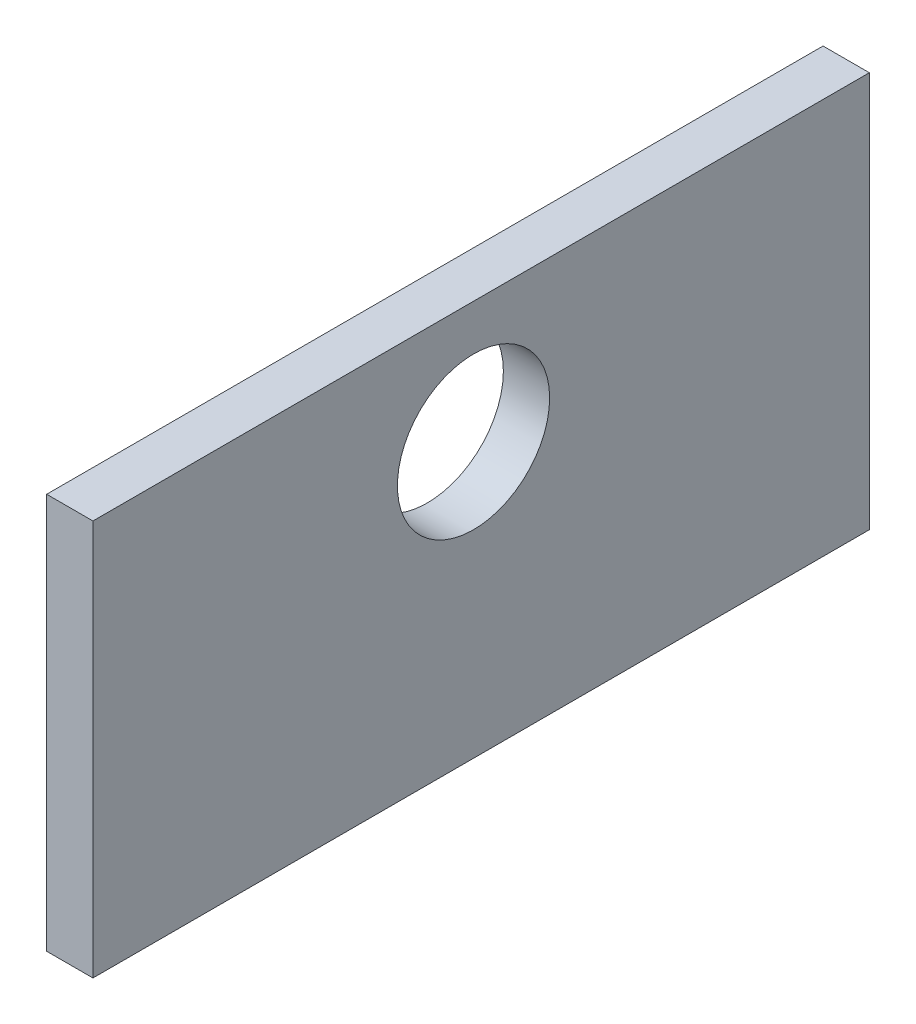
SolidWorks part; units mm, degrees
material "6061 Alloy"
ref_plane "Front Plane" through (0, 0, 0) normal (0, 0, 1) x (1, 0, 0)
ref_plane "Top Plane" through (0, 0, 0) normal (0, 1, 0) x (1, 0, 0)
ref_plane "Right Plane" through (0, 0, 0) normal (1, 0, 0) x (0, 0, -1)
sketch "Sketch1" plane through (0, 0, 0) normal (1, 0, 0) x (0, 0, -1)
  line L0 (0, -28.575) -> (0, 12.7) construction
  line L1 (-39.6875, 12.7) -> (41.275, 12.7)
  line L2 (-39.6875, 12.7) -> (-39.6875, -28.575)
  line L3 (-39.6875, -28.575) -> (41.275, -28.575)
  line L4 (41.275, 12.7) -> (41.275, -28.575)
  circle A0 centre (0, 0) radius 7.9375
  dimension "D3" = 15.875
  dimension "D1" = 41.275
  dimension "D2" = 12.7
  dimension "D4" = 28.575
  dimension "D5" = 39.6875
extrude "Boss-Extrude1" add sketch "Sketch1" along normal blind 4.826
